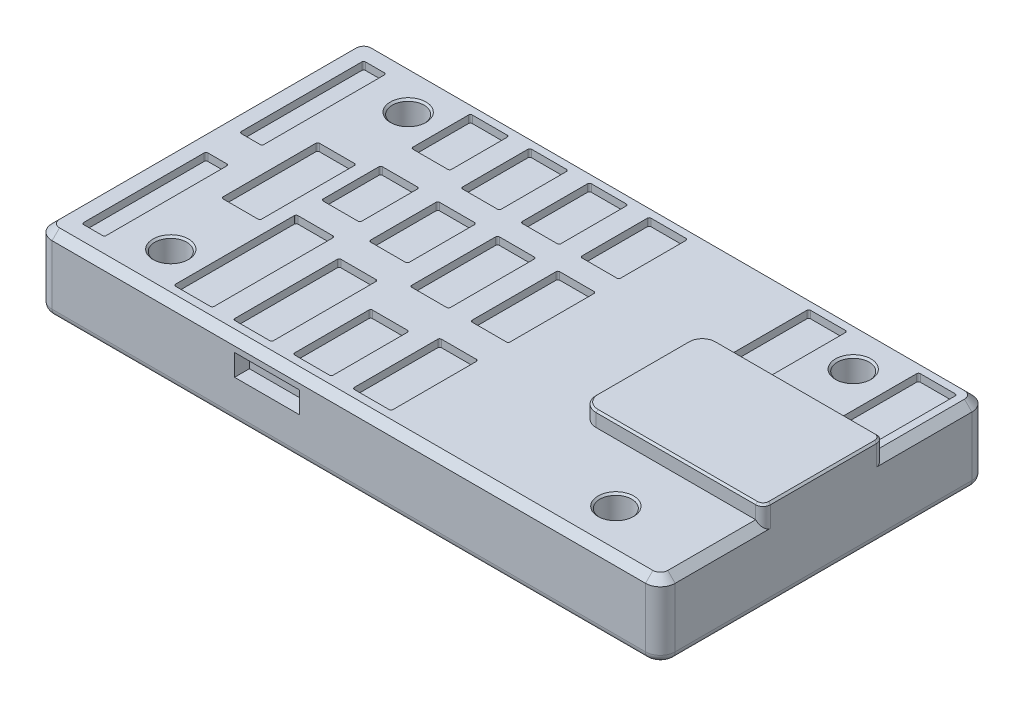
SolidWorks part; units mm, degrees
material "1060 Alloy"
ref_plane "Front Plane" through (0, 0, 0) normal (0, 0, 1) x (1, 0, 0)
ref_plane "Top Plane" through (0, 0, 0) normal (0, 1, 0) x (1, 0, 0)
ref_plane "Right Plane" through (0, 0, 0) normal (1, 0, 0) x (0, 0, -1)
sketch "Sketch1" plane through (0, 0, 0) normal (0, 1, 0) x (1, 0, 0)
  line L1 (-42, -22) -> (42, -22)
  line L2 (-42, -22) -> (-42, 22)
  line L3 (-42, 22) -> (42, 22)
  line L4 (42, -22) -> (42, 22)
  line L5 (-42, -22) -> (42, 22) construction
  line L6 (-42, 22) -> (42, -22) construction
  point P0 (0, 0)
  dimension "D1" = 84
  dimension "D2" = 44
extrude "Boss-Extrude1" add sketch "Sketch1" along normal blind 10
sketch "Sketch2" plane through (0, 10, 0) normal (0, 1, 0) x (1, 0, 0)
  line L0 (42, -22) -> (42, 22) construction
  line L1 (42, 8.15) -> (17.5, 8.15)
  line L2 (42, 8.15) -> (42, -8.15)
  line L3 (42, -8.15) -> (17.5, -8.15)
  line L4 (17.5, 8.15) -> (17.5, -8.15)
  point P6 (17.5, 0)
  dimension "D1" = 24.5
  dimension "D2" = 16.3
extrude "Boss-Extrude2" add sketch "Sketch2" along normal blind 2
fillet "Fillet1" radius 2 2 edges at (17.5, 11, -8.15) (17.5, 11, 8.15)
fillet "Fillet2" radius 2 4 edges at (-42, 5, -22) (-42, 5, 22) (42, 5, -22) (42, 5, 22)
fillet "Fillet3" radius 1 8 edges at (-41.4142, 0, 21.4142) (0, 0, 22) (41.4142, 0, 21.4142) (42, 0, 0) (41.4142, 0, -21.4142) (0, 0, -22) (-41.4142, 0, -21.4142) (-42, 0, 0)
fillet "Fillet4" radius 1 2 edges at (42, 11, -8.15) (42, 11, 8.15)
chamfer "Chamfer1" distance 1 angle 45 9 edges at (42, 10, 13.575) (41.4142, 10, 21.4142) (0, 10, 22) (-41.4142, 10, 21.4142) (42, 10, -13.575) (-42, 10, 0) (41.4142, 10, -21.4142) (-41.4142, 10, -21.4142) (0, 10, -22)
sketch "Sketch3" plane through (0, 0, 0) normal (0, -1, 0) x (1, 0, 0)
  circle A0 centre (30, 16) radius 0.875
  dimension "D1" = 1.75
  dimension "D2" = 30
  dimension "D3" = 16
extrude "Cut-Extrude1" cut sketch "Sketch3" against normal through all
sketch "Sketch4" plane through (0, 10, 0) normal (0, 1, 0) x (1, 0, 0)
  circle A0 centre (30, -16) radius 2.15
  dimension "D1" = 4.3
extrude "Cut-Extrude2" cut sketch "Sketch4" against normal blind 5
mirror "Mirror2" about plane through (0, 0, 0) normal (0, 0, 1) of "Cut-Extrude2", "Cut-Extrude1"
mirror "Mirror3" about plane through (0, 0, 0) normal (1, 0, 0) of "Mirror2", "Cut-Extrude1", "Cut-Extrude2"
chamfer "Chamfer4" distance 0.25 angle 45 12 edges at (30.25, 12, -8.15) (18.0858, 12, -7.5642) (41.7071, 12, -7.8571) (17.5, 12, 0) (42, 12, 0) (18.0858, 12, 7.5642) (41.7071, 12, 7.8571) (30.25, 12, 8.15) (-30, 10, 18.15) (-30, 10, -18.15) (30, 10, -18.15) (30, 10, 18.15)
sketch "Sketch5" plane through (0, 10, 0) normal (0, 1, 0) x (1, 0, 0)
  line L1 (39.75, 20) -> (35.05, 20)
  line L2 (40, 19.75) -> (40, 8.5)
  line L3 (39.75, 8.25) -> (35.05, 8.25)
  line L4 (34.8, 19.75) -> (34.8, 8.5)
  line L5 (24.95, 20) -> (20.25, 20)
  line L6 (25.2, 19.75) -> (25.2, 8.5)
  line L7 (24.95, 8.25) -> (20.25, 8.25)
  line L8 (20, 19.75) -> (20, 8.5)
  line L9 (3.4444, 20) -> (-1.2556, 20)
  line L10 (3.6944, 19.75) -> (3.6944, 10.95)
  line L11 (3.4444, 10.7) -> (-1.2556, 10.7)
  line L12 (-1.5056, 19.75) -> (-1.5056, 10.95)
  line L13 (-4.6056, 20) -> (-9.3056, 20)
  line L14 (-4.3556, 19.75) -> (-4.3556, 10.95)
  line L15 (-4.6056, 10.7) -> (-9.3056, 10.7)
  line L16 (-9.5556, 19.75) -> (-9.5556, 10.95)
  line L17 (-12.6556, 20) -> (-17.3556, 20)
  line L18 (-12.4056, 19.75) -> (-12.4056, 10.95)
  line L19 (-12.6556, 10.7) -> (-17.3556, 10.7)
  line L20 (-17.6056, 19.75) -> (-17.6056, 10.95)
  arc A0 (39.75, 8.25) -> (40, 8.5) centre (39.75, 8.5) ccw
  arc A1 (35.05, 8.25) -> (34.8, 8.5) centre (35.05, 8.5) cw
  arc A2 (34.8, 19.75) -> (35.05, 20) centre (35.05, 19.75) cw
  arc A3 (40, 19.75) -> (39.75, 20) centre (39.75, 19.75) ccw
  arc A4 (24.95, 8.25) -> (25.2, 8.5) centre (24.95, 8.5) ccw
  circle A5 centre (30, 16) radius 2.4 construction
  arc A6 (20.25, 8.25) -> (20, 8.5) centre (20.25, 8.5) cw
  arc A7 (20, 19.75) -> (20.25, 20) centre (20.25, 19.75) cw
  arc A8 (24.95, 20) -> (25.2, 19.75) centre (24.95, 19.75) cw
  arc A9 (-1.2556, 20) -> (-1.5056, 19.75) centre (-1.2556, 19.75) ccw
  arc A10 (-1.5056, 10.95) -> (-1.2556, 10.7) centre (-1.2556, 10.95) ccw
  arc A11 (3.4444, 10.7) -> (3.6944, 10.95) centre (3.4444, 10.95) ccw
  arc A12 (3.6944, 19.75) -> (3.4444, 20) centre (3.4444, 19.75) ccw
  arc A13 (-9.5556, 10.95) -> (-9.3056, 10.7) centre (-9.3056, 10.95) ccw
  arc A14 (-4.6056, 10.7) -> (-4.3556, 10.95) centre (-4.6056, 10.95) ccw
  arc A15 (-4.3556, 19.75) -> (-4.6056, 20) centre (-4.6056, 19.75) ccw
  arc A16 (-9.3056, 20) -> (-9.5556, 19.75) centre (-9.3056, 19.75) ccw
  arc A17 (-17.6056, 10.95) -> (-17.3556, 10.7) centre (-17.3556, 10.95) ccw
  arc A18 (-12.6556, 10.7) -> (-12.4056, 10.95) centre (-12.6556, 10.95) ccw
  arc A19 (-12.4056, 19.75) -> (-12.6556, 20) centre (-12.6556, 19.75) ccw
  arc A20 (-17.3556, 20) -> (-17.6056, 19.75) centre (-17.3556, 19.75) ccw
  point P7 (40, 8.25)
  point P12 (34.8, 20)
  point P15 (40, 20)
  point P24 (25.2, 8.25)
  point P29 (20, 20)
  point P32 (25.2, 20)
  point P39 (-1.5056, 20)
  point P44 (3.6944, 10.7)
  point P47 (3.6944, 20)
  point P62 (-4.3556, 20)
  point P65 (-9.5556, 20)
  point P72 (-12.4056, 20)
  point P75 (-17.6056, 20)
  dimension "D3" = 0.25
  dimension "D6" = 4.8
  dimension "D7" = 0.25
  dimension "D10" = 0.25
  dimension "D15" = 0.25
  dimension "D1" = 11.75
  dimension "D2" = 5.2
  dimension "D4" = 11.75
  dimension "D5" = 5.2
  dimension "D8" = 5.2
  dimension "D9" = 9.3
  dimension "D11" = 5.2
  dimension "D12" = 2.85
  dimension "D13" = 5.2
  dimension "D14" = 2.85
extrude "Cut-Extrude3" cut sketch "Sketch5" against normal blind 1
sketch "Sketch6" plane through (0, 10, 0) normal (0, 1, 0) x (1, 0, 0)
  line L0 (-12.4056, 10.95) -> (-12.4056, 19.75) construction
  line L5 (3.4444, -20) -> (-1.2556, -20)
  line L6 (3.6944, -19.75) -> (3.6944, -8.5)
  line L7 (3.4444, -8.25) -> (-1.2556, -8.25)
  line L8 (-1.5056, -19.75) -> (-1.5056, -8.5)
  line L9 (-4.6056, -20) -> (-9.3056, -20)
  line L10 (-4.3556, -19.75) -> (-4.3556, -9.75)
  line L11 (-4.6056, -9.5) -> (-9.3056, -9.5)
  line L12 (-9.5556, -19.75) -> (-9.5556, -9.75)
  line L13 (-12.6556, -20) -> (-17.3556, -20)
  line L14 (-12.4056, -19.75) -> (-12.4056, -5.95)
  line L15 (-12.6556, -5.7) -> (-17.3556, -5.7)
  line L16 (-17.6056, -19.75) -> (-17.6056, -5.95)
  line L17 (-20.6556, -20) -> (-25.3556, -20)
  line L18 (-20.4056, -19.75) -> (-20.4056, -3.75)
  line L19 (-20.6556, -3.5) -> (-25.3556, -3.5)
  line L20 (-25.6056, -19.75) -> (-25.6056, -3.75)
  line L21 (3.6944, 10.95) -> (3.6944, 19.75) construction
  line L24 (-12.6556, 20) -> (-17.3556, 20) construction
  line L25 (-20.6556, -0.1) -> (-25.3556, -0.1)
  line L26 (-20.4056, 0.15) -> (-20.4056, 7.65)
  line L27 (-20.6556, 7.9) -> (-25.3556, 7.9)
  line L28 (-25.6056, 0.15) -> (-25.6056, 7.65)
  line L29 (-20.6556, 20) -> (-25.3556, 20)
  line L30 (-20.4056, 19.75) -> (-20.4056, 12.25)
  line L31 (-20.6556, 12) -> (-25.3556, 12)
  line L32 (-25.6056, 19.75) -> (-25.6056, 12.25)
  arc A0 (-25.3556, -3.5) -> (-25.6056, -3.75) centre (-25.3556, -3.75) ccw
  arc A1 (-25.6056, -19.75) -> (-25.3556, -20) centre (-25.3556, -19.75) ccw
  arc A2 (-20.6556, -20) -> (-20.4056, -19.75) centre (-20.6556, -19.75) ccw
  arc A3 (-20.4056, -3.75) -> (-20.6556, -3.5) centre (-20.6556, -3.75) ccw
  arc A4 (-17.3556, -5.7) -> (-17.6056, -5.95) centre (-17.3556, -5.95) ccw
  arc A5 (-17.6056, -19.75) -> (-17.3556, -20) centre (-17.3556, -19.75) ccw
  arc A6 (-12.6556, -20) -> (-12.4056, -19.75) centre (-12.6556, -19.75) ccw
  arc A7 (-12.4056, -5.95) -> (-12.6556, -5.7) centre (-12.6556, -5.95) ccw
  arc A8 (-9.3056, -9.5) -> (-9.5556, -9.75) centre (-9.3056, -9.75) ccw
  arc A9 (-9.5556, -19.75) -> (-9.3056, -20) centre (-9.3056, -19.75) ccw
  arc A10 (-4.6056, -20) -> (-4.3556, -19.75) centre (-4.6056, -19.75) ccw
  arc A11 (-4.3556, -9.75) -> (-4.6056, -9.5) centre (-4.6056, -9.75) ccw
  arc A12 (3.6944, -8.5) -> (3.4444, -8.25) centre (3.4444, -8.5) ccw
  arc A13 (-1.2556, -8.25) -> (-1.5056, -8.5) centre (-1.2556, -8.5) ccw
  arc A14 (-1.5056, -19.75) -> (-1.2556, -20) centre (-1.2556, -19.75) ccw
  arc A15 (3.4444, -20) -> (3.6944, -19.75) centre (3.4444, -19.75) ccw
  arc A16 (-20.6556, -0.1) -> (-20.4056, 0.15) centre (-20.6556, 0.15) ccw
  arc A17 (-25.3556, 7.9) -> (-25.6056, 7.65) centre (-25.3556, 7.65) ccw
  arc A18 (-25.6056, 0.15) -> (-25.3556, -0.1) centre (-25.3556, 0.15) ccw
  arc A19 (-20.4056, 7.65) -> (-20.6556, 7.9) centre (-20.6556, 7.65) ccw
  arc A20 (-25.3556, 20) -> (-25.6056, 19.75) centre (-25.3556, 19.75) ccw
  arc A21 (-25.6056, 12.25) -> (-25.3556, 12) centre (-25.3556, 12.25) ccw
  arc A22 (-20.6556, 12) -> (-20.4056, 12.25) centre (-20.6556, 12.25) ccw
  arc A23 (-20.6556, 20) -> (-20.4056, 19.75) centre (-20.6556, 19.75) cw
  point P29 (-25.6056, -20)
  point P32 (-20.4056, -20)
  point P35 (-20.4056, -3.5)
  point P40 (-17.6056, -20)
  point P43 (-12.4056, -20)
  point P46 (-12.4056, -5.7)
  point P51 (-9.5556, -20)
  point P54 (-4.3556, -20)
  point P57 (-4.3556, -9.5)
  point P60 (3.6944, -8.25)
  point P65 (-1.5056, -20)
  point P68 (3.6944, -20)
  point P77 (-20.4056, -0.1)
  point P84 (-20.4056, 7.9)
  point P91 (-20.4056, 12)
  point P94 (-20.4056, 20)
  dimension "D10" = 0.25
  dimension "D14" = 0.25
  dimension "D1" = 11.75
  dimension "D2" = 5.2
  dimension "D3" = 10.5
  dimension "D4" = 5.2
  dimension "D5" = 14.3
  dimension "D6" = 5.2
  dimension "D7" = 16.5
  dimension "D8" = 5.2
  dimension "D9" = 2.8
  dimension "D11" = 8
  dimension "D12" = 3.4
  dimension "D13" = 8
extrude "Cut-Extrude4" cut sketch "Sketch6" against normal blind 1
sketch "Sketch7" plane through (0, 10, 0) normal (0, 1, 0) x (1, 0, 0)
  line L0 (-1.2556, 10.7) -> (3.4444, 10.7) construction
  line L1 (3.4444, 7.6) -> (-1.164, 7.6)
  line L2 (3.6944, 7.35) -> (3.6944, -3.95)
  line L3 (3.4444, -4.2) -> (-1.164, -4.2)
  line L4 (-1.414, 7.35) -> (-1.414, -3.95)
  line L6 (-4.6056, 7.6) -> (-9.3056, 7.6)
  line L7 (-4.3556, 7.35) -> (-4.3556, -3.95)
  line L8 (-4.6056, -4.2) -> (-9.3056, -4.2)
  line L9 (-9.5556, 7.35) -> (-9.5556, -3.95)
  line L10 (3.6944, 10.95) -> (3.6944, 19.75) construction
  line L11 (-17.3556, 10.7) -> (-12.6556, 10.7) construction
  line L12 (-12.6556, 7.6) -> (-17.3556, 7.6)
  line L13 (-12.4056, 7.35) -> (-12.4056, -1.45)
  line L14 (-12.6556, -1.7) -> (-17.3556, -1.7)
  line L15 (-17.6056, 7.35) -> (-17.6056, -1.45)
  line L16 (-12.4056, 10.95) -> (-12.4056, 19.75) construction
  arc A0 (-1.164, 7.6) -> (-1.414, 7.35) centre (-1.164, 7.35) ccw
  arc A1 (-1.414, -3.95) -> (-1.164, -4.2) centre (-1.164, -3.95) ccw
  arc A2 (3.4444, -4.2) -> (3.6944, -3.95) centre (3.4444, -3.95) ccw
  arc A3 (3.6944, 7.35) -> (3.4444, 7.6) centre (3.4444, 7.35) ccw
  arc A4 (-12.6556, 7.6) -> (-12.4056, 7.35) centre (-12.6556, 7.35) cw
  arc A5 (-12.4056, -1.45) -> (-12.6556, -1.7) centre (-12.6556, -1.45) cw
  arc A6 (-17.3556, -1.7) -> (-17.6056, -1.45) centre (-17.3556, -1.45) cw
  arc A7 (-17.6056, 7.35) -> (-17.3556, 7.6) centre (-17.3556, 7.35) cw
  arc A8 (-9.3056, 7.6) -> (-9.5556, 7.35) centre (-9.3056, 7.35) ccw
  arc A9 (-9.5556, -3.95) -> (-9.3056, -4.2) centre (-9.3056, -3.95) ccw
  arc A10 (-4.6056, -4.2) -> (-4.3556, -3.95) centre (-4.6056, -3.95) ccw
  arc A11 (-4.3556, 7.35) -> (-4.6056, 7.6) centre (-4.6056, 7.35) ccw
  point P26 (3.6944, -4.2)
  point P29 (3.6944, 7.6)
  point P32 (-12.4056, 7.6)
  point P35 (-12.4056, -1.7)
  point P38 (-17.6056, -1.7)
  point P45 (-9.5556, -4.2)
  point P48 (-4.3556, -4.2)
  dimension "D7" = 0.25
  dimension "D1" = 3.1
  dimension "D2" = 11.8
  dimension "D3" = 5.2
  dimension "D4" = 9.3
  dimension "D5" = 3.1
  dimension "D6" = 5.2
extrude "Cut-Extrude5" cut sketch "Sketch7" against normal blind 1
sketch "Sketch8" plane through (0, 10, 0) normal (0, 1, 0) x (1, 0, 0)
  line L0 (-42, -20) -> (-42, 20) construction
  line L1 (-27.65, 6.4012) -> (-32.35, 6.4012)
  line L2 (-27.4, 6.1512) -> (-27.4, -6.3488)
  line L3 (-27.65, -6.5988) -> (-32.35, -6.5988)
  line L4 (-32.6, 6.1512) -> (-32.6, -6.3488)
  line L5 (-27.4, 6.4012) -> (-32.6, -6.5988) construction
  line L6 (-27.4, -6.5988) -> (-32.6, 6.4012) construction
  line L7 (-38.75, 19) -> (-36.2044, 19)
  line L8 (-39, 18.75) -> (-39, 2.5)
  line L9 (-38.75, 2.25) -> (-36.2044, 2.25)
  line L10 (-35.9544, 18.75) -> (-35.9544, 2.5)
  line L11 (-40, 22) -> (40, 22) construction
  line L12 (40, -22) -> (-40, -22) construction
  line L13 (-36.2044, -2.25) -> (-38.75, -2.25)
  line L14 (-35.9544, -2.5) -> (-35.9544, -18.75)
  line L15 (-36.2044, -19) -> (-38.75, -19)
  line L16 (-39, -2.5) -> (-39, -18.75)
  arc A0 (-35.9544, -18.75) -> (-36.2044, -19) centre (-36.2044, -18.75) cw
  arc A1 (-38.75, -19) -> (-39, -18.75) centre (-38.75, -18.75) cw
  arc A2 (-39, -2.5) -> (-38.75, -2.25) centre (-38.75, -2.5) cw
  arc A3 (-35.9544, -2.5) -> (-36.2044, -2.25) centre (-36.2044, -2.5) ccw
  arc A4 (-35.9544, 2.5) -> (-36.2044, 2.25) centre (-36.2044, 2.5) cw
  arc A5 (-38.75, 2.25) -> (-39, 2.5) centre (-38.75, 2.5) cw
  arc A6 (-39, 18.75) -> (-38.75, 19) centre (-38.75, 18.75) cw
  arc A7 (-35.9544, 18.75) -> (-36.2044, 19) centre (-36.2044, 18.75) ccw
  arc A8 (-32.35, 6.4012) -> (-32.6, 6.1512) centre (-32.35, 6.1512) ccw
  arc A9 (-32.6, -6.3488) -> (-32.35, -6.5988) centre (-32.35, -6.3488) ccw
  arc A10 (-27.65, -6.5988) -> (-27.4, -6.3488) centre (-27.65, -6.3488) ccw
  arc A11 (-27.4, 6.1512) -> (-27.65, 6.4012) centre (-27.65, 6.1512) ccw
  point P0 (-30, -0.0988)
  point P12 (-37.4772, 19)
  point P25 (-39, -19)
  point P28 (-39, -2.25)
  point P35 (-39, 2.25)
  point P38 (-39, 19)
  dimension "D10" = 0.25
  dimension "D1" = 5.2
  dimension "D2" = 13
  dimension "D3" = 30
  dimension "D4" = 16.75
  dimension "D5" = 3
  dimension "D6" = 3
  dimension "D7" = 16.75
  dimension "D8" = 3
  dimension "D9" = 3
extrude "Cut-Extrude6" cut sketch "Sketch8" against normal blind 1
sketch "Sketch9" plane through (-42, 0, 0) normal (-1, 0, 0) x (0, 0, 1)
  line L0 (-22, 1) -> (-22, 9) construction
  line L1 (-8.5, 4.4) -> (5.5, 4.4)
  line L2 (-8.5, 4.4) -> (-8.5, 2.1)
  line L3 (-8.5, 2.1) -> (5.5, 2.1)
  line L4 (5.5, 4.4) -> (5.5, 2.1)
  line L5 (20, 0) -> (-20, 0) construction
  dimension "D1" = 2.3
  dimension "D2" = 14
  dimension "D3" = 13.5
  dimension "D4" = 2.1
extrude "Cut-Extrude7" cut sketch "Sketch9" against normal blind 5
sketch "Sketch10" plane through (0, 0, 22) normal (0, 0, 1) x (1, 0, 0)
  line L0 (-40, 10) -> (40, 10) construction
  line L1 (-15.4, 8.25) -> (-6.65, 8.25)
  line L2 (-15.4, 8.25) -> (-15.4, 5.35)
  line L3 (-15.4, 5.35) -> (-6.65, 5.35)
  line L4 (-6.65, 8.25) -> (-6.65, 5.35)
  line L5 (-42, 1) -> (-42, 9) construction
  dimension "D1" = 8.75
  dimension "D2" = 2.9
  dimension "D3" = 1.75
  dimension "D4" = 26.6
extrude "Cut-Extrude8" cut sketch "Sketch10" against normal blind 2
